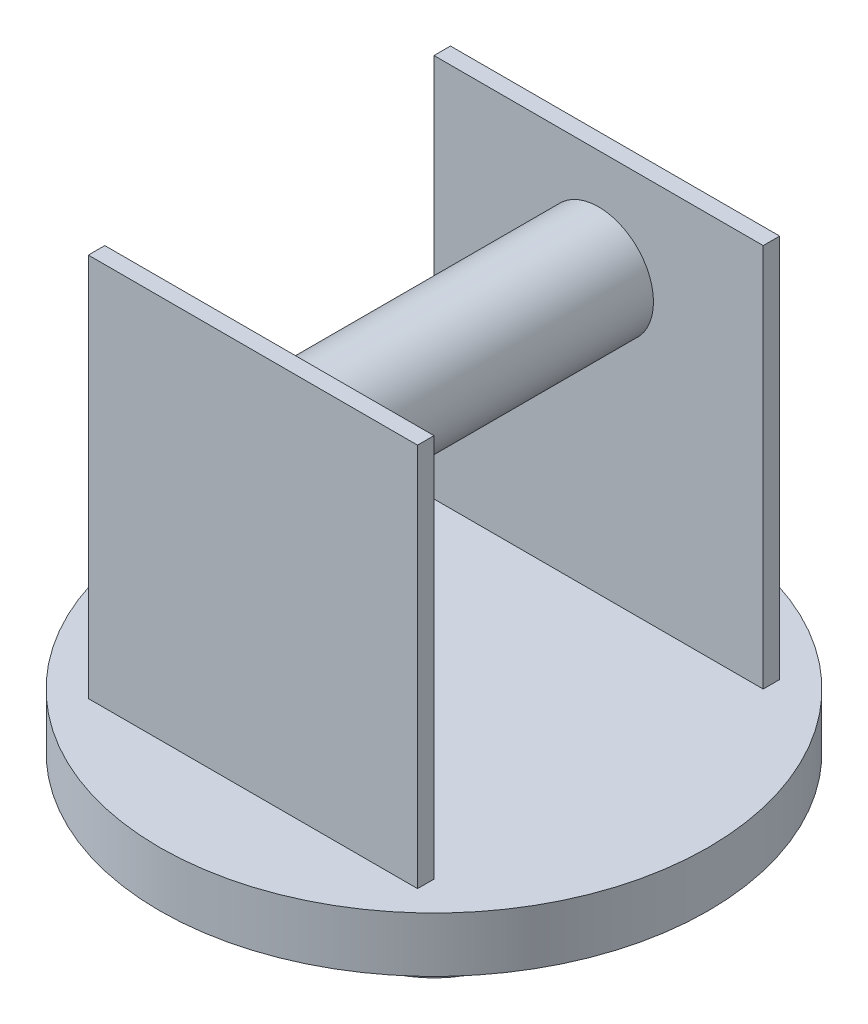
SolidWorks part; units mm, degrees
material "ENPH 253 Hardboard"
ref_plane "Front Plane" through (0, 0, 0) normal (0, 0, 1) x (1, 0, 0)
ref_plane "Top Plane" through (0, 0, 0) normal (0, 1, 0) x (1, 0, 0)
ref_plane "Right Plane" through (0, 0, 0) normal (1, 0, 0) x (0, 0, -1)
sketch "Sketch1" plane through (0, 0, 0) normal (0, 1, 0) x (1, 0, 0)
  circle A0 centre (0, 0) radius 50
  dimension "D1" = 100
extrude "Boss-Extrude1" add sketch "Sketch1" along normal blind 10
sketch "Sketch2" plane through (0, 0, 0) normal (0, -1, 0) x (-1, 0, 0)
  circle A0 centre (0, 0) radius 15
  dimension "D1" = 30
extrude "Boss-Extrude2" add sketch "Sketch2" along normal blind 25
sketch "Sketch3" plane through (0, 10, 0) normal (0, 1, 0) x (1, 0, 0)
  line L1 (-30, -33) -> (30, -33)
  line L2 (-30, -33) -> (-30, -30)
  line L3 (-30, -30) -> (30, -30)
  line L4 (30, -33) -> (30, -30)
  line L5 (-30, 30) -> (30, 30)
  line L6 (-30, 30) -> (-30, 33)
  line L7 (-30, 33) -> (30, 33)
  line L8 (30, 30) -> (30, 33)
  dimension "D1" = 60
  dimension "D2" = 3
  dimension "D5" = 30
  dimension "D6" = 30
  dimension "D7" = 30
  dimension "D3" = 30
extrude "Boss-Extrude3" add sketch "Sketch3" along normal blind 70
sketch "Sketch4" plane through (0, 0, 33) normal (0, 0, 1) x (1, 0, 0)
  circle A0 centre (0, 61.1108) radius 10
extrude "Boss-Extrude4" add sketch "Sketch4" against normal up to surface (63 mm away) up to face at (0, 45, -30)
equation "\"D7@Sketch3\"=\"D1@Sketch3\"/2"
equation "\"D3@Sketch3\"=\"D7@Sketch3\""
